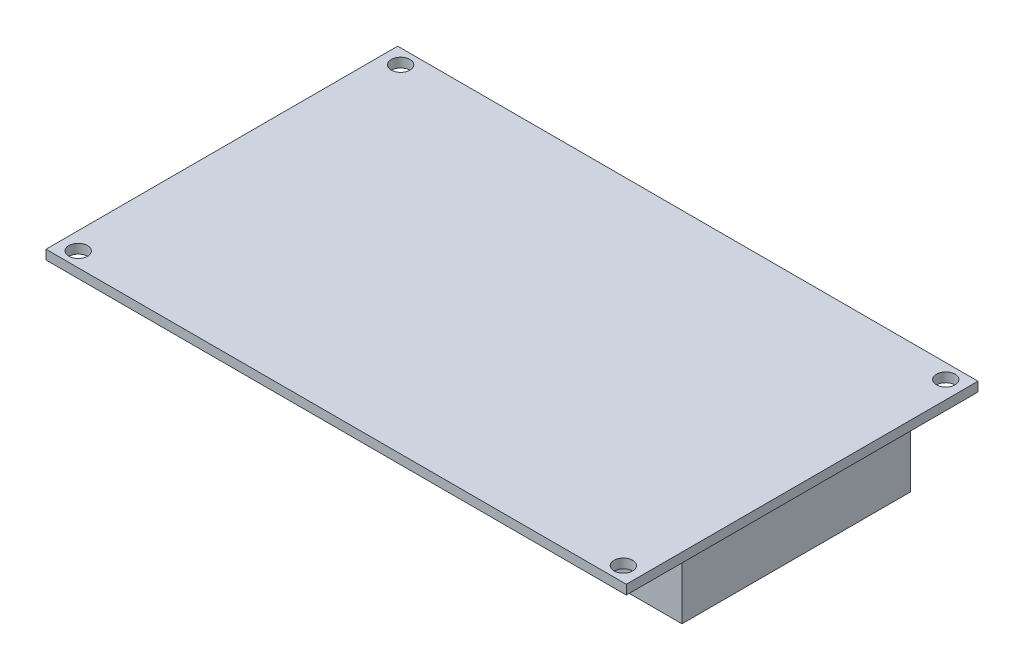
SolidWorks part; units mm, degrees
material "ABS"
ref_plane "Ground_Plane" through (0, 0, 0) normal (0, 0, 1) x (1, 0, 0)
ref_plane "VehicleCentre_Plane" through (0, 0, 0) normal (0, 1, 0) x (1, 0, 0)
ref_plane "FrontAxle_Plane" through (0, 0, 0) normal (1, 0, 0) x (0, 0, -1)
sketch "Sketch1" plane through (0, 0, 0) normal (0, 1, 0) x (1, 0, 0)
  line L1 (49.5, -30) -> (-49.5, -30)
  line L2 (49.5, -30) -> (49.5, 30)
  line L3 (49.5, 30) -> (-49.5, 30)
  line L4 (-49.5, -30) -> (-49.5, 30)
  line L5 (49.5, -30) -> (-49.5, 30) construction
  line L6 (49.5, 30) -> (-49.5, -30) construction
  point P0 (0, 0)
  dimension "D1" = 60
  dimension "D2" = 99
extrude "Boss-Extrude1" add sketch "Sketch1" along normal blind 1.6
sketch "Sketch2" plane through (0, 0, 0) normal (0, -1, 0) x (1, 0, 0)
  circle A0 centre (-46.5, 27.5) radius 1.5875
  circle A1 centre (46.5, 27.5) radius 1.5875
  circle A2 centre (46.5, -27.5) radius 1.5875
  circle A3 centre (-46.5, -27.5) radius 1.5875
extrude "Cut-Extrude1" cut sketch "Sketch2" against normal through all
sketch "Sketch3" plane through (0, 0, 0) normal (0, -1, 0) x (1, 0, 0)
  line L1 (48.5, 19.5) -> (-48.5, 19.5)
  line L2 (48.5, 19.5) -> (48.5, -19.5)
  line L3 (48.5, -19.5) -> (-48.5, -19.5)
  line L4 (-48.5, 19.5) -> (-48.5, -19.5)
  line L5 (48.5, 19.5) -> (-48.5, -19.5) construction
  line L6 (48.5, -19.5) -> (-48.5, 19.5) construction
  point P0 (0, 0)
  dimension "D1" = 39
  dimension "D2" = 97
extrude "Boss-Extrude2" add sketch "Sketch3" along normal blind 10 separate body
sketch "Sketch4" plane through (0, -10, 0) normal (0, -1, 0) x (1, 0, 0)
  line L1 (35.5, 13) -> (-35.5, 13)
  line L2 (35.5, 13) -> (35.5, -13)
  line L3 (35.5, -13) -> (-35.5, -13)
  line L4 (-35.5, 13) -> (-35.5, -13)
  line L5 (35.5, 13) -> (-35.5, -13) construction
  line L6 (35.5, -13) -> (-35.5, 13) construction
  point P0 (0, 0)
  dimension "D1" = 26
  dimension "D2" = 71
extrude "Cut-Extrude2" cut sketch "Sketch4" against normal blind 0.5
sketch "Sketch5" plane through (0, -9.5, 0) normal (0, -1, 0) x (1, 0, 0)
  text T0 "<b>OVEN CONTROL ELEMENTS</b>\r\n<b>GROUP 41</b>\r\n\r\n<b>PROUDLY FUNDED BY WEEF</b>"
split line "Split Line1"
equation "\"D3@Sketch2\"=\"D2@Sketch2\"*0.5"
equation "\"D4@Sketch2\"=\"D1@Sketch2\"*0.5"
